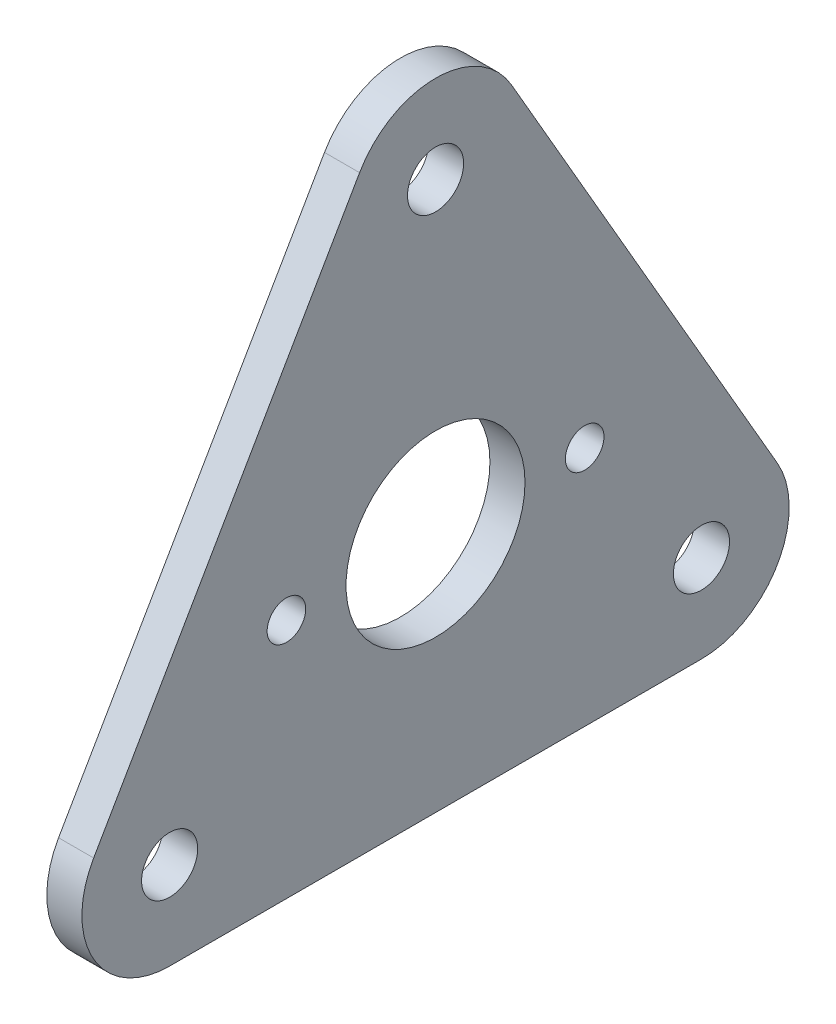
SolidWorks part; units mm, degrees
material "5052-H34"
ref_plane "正面" through (0, 0, 0) normal (0, 0, 1) x (1, 0, 0)
ref_plane "平面" through (0, 0, 0) normal (0, 1, 0) x (1, 0, 0)
ref_plane "右側面" through (0, 0, 0) normal (1, 0, 0) x (0, 0, -1)
sketch "ｽｹｯﾁ1" plane through (0, 0, 0) normal (1, 0, 0) x (0, 0, -1)
  line L0 (0, 0) -> (0, 17.5) construction
  line L1 (0, 0) -> (-8.5, 0) construction
  line L2 (-4.3301, 20) -> (-19.4856, -6.25)
  line L3 (19.4856, -6.25) -> (4.3301, 20)
  line L4 (-15.1554, -13.75) -> (15.1554, -13.75)
  circle A0 centre (0, 0) radius 11.25 construction
  circle A1 centre (0, 0) radius 5.1
  circle A2 centre (0, 17.5) radius 1.6
  circle A3 centre (-8.5, 0) radius 1.1
  circle A4 centre (8.5, 0) radius 1.1
  circle A5 centre (15.1554, -8.75) radius 1.6
  arc A6 (-15.8913, -7.3292) -> (-14.2929, -10.0976) centre (-15.1554, -8.75) ccw
  circle A7 centre (0, 0) radius 17.5 construction
  circle A8 centre (0, 17.5) radius 3.5 construction
  arc A9 (15.1554, -13.75) -> (19.4856, -6.25) centre (15.1554, -8.75) ccw
  arc A10 (-19.4856, -6.25) -> (-15.1554, -13.75) centre (-15.1554, -8.75) ccw
  arc A11 (4.3301, 20) -> (-4.3301, 20) centre (0, 17.5) ccw
  arc A12 (-12.0625, -12.6786) -> (-17.0112, -4.1071) centre (-15.1554, -8.75) ccw construction
  arc A13 (-14.2929, -10.0976) -> (-15.8913, -7.3292) centre (-15.1554, -8.75) ccw
  arc A14 (-17.0112, -4.1071) -> (-19.4856, -6.25) centre (-15.1554, -8.75) ccw construction
  arc A15 (-15.1554, -13.75) -> (-12.0625, -12.6786) centre (-15.1554, -8.75) ccw construction
  arc A16 (17.0112, -4.1071) -> (12.0625, -12.6786) centre (15.1554, -8.75) ccw construction
  arc A17 (19.4856, -6.25) -> (17.0112, -4.1071) centre (15.1554, -8.75) ccw construction
  arc A18 (12.0625, -12.6786) -> (15.1554, -13.75) centre (15.1554, -8.75) ccw construction
  arc A19 (0, 12.5) -> (4.9487, 16.7857) centre (0, 17.5) ccw construction
  arc A20 (4.9487, 16.7857) -> (4.3301, 20) centre (0, 17.5) ccw construction
  arc A21 (-4.9487, 16.7857) -> (0, 12.5) centre (0, 17.5) ccw construction
  arc A22 (-4.3301, 20) -> (-4.9487, 16.7857) centre (0, 17.5) ccw construction
  dimension "D1" = 22.5
  dimension "D2" = 10.2
  dimension "D3" = 3.2
  dimension "D4" = 2.2
  dimension "D7" = 35
  dimension "D8" = 7
  dimension "D9" = 10
  dimension "D5" = 17
  dimension "D6" = 3
  dimension "D10" = 3
  dimension "D11" = 3
extrude "ﾎﾞｽ - 押し出し1" add sketch "ｽｹｯﾁ1" along normal blind 2
